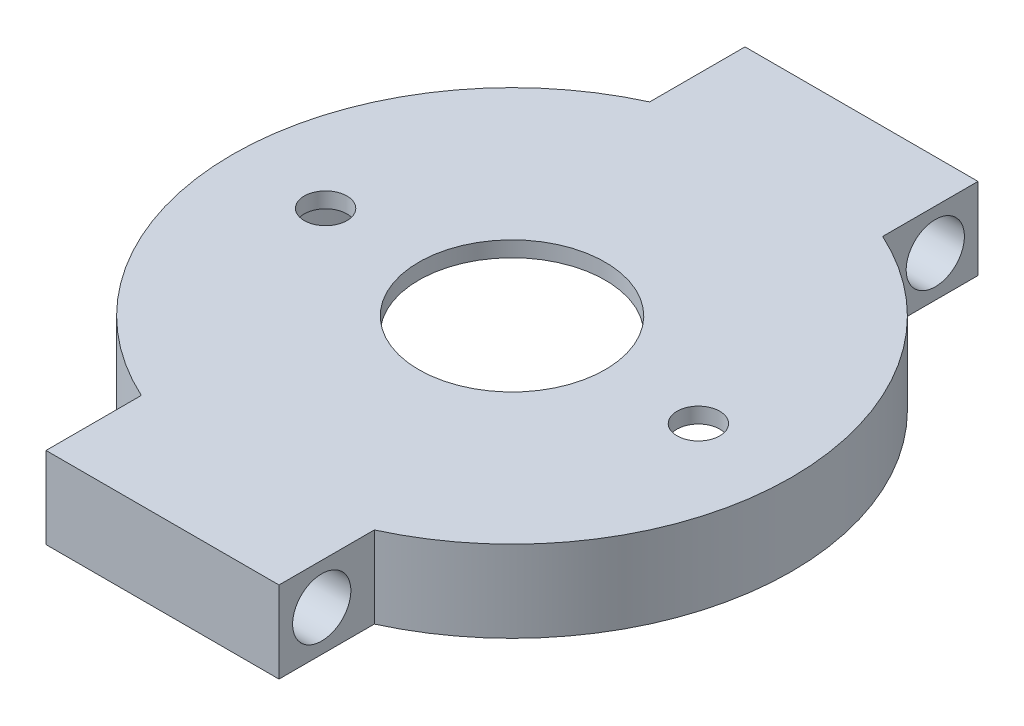
SolidWorks part; units mm, degrees
material "1345 Alloy"
ref_plane "Front Plane" through (0, 0, 0) normal (0, 0, 1) x (1, 0, 0)
ref_plane "Top Plane" through (0, 0, 0) normal (0, 1, 0) x (1, 0, 0)
ref_plane "Right Plane" through (0, 0, 0) normal (1, 0, 0) x (0, 0, -1)
sketch "Sketch1" plane through (0, 0, 0) normal (0, 1, 0) x (1, 0, 0)
  line L0 (-19.05, 57.15) -> (19.05, 57.15)
  line L1 (-19.05, -57.15) -> (19.05, -57.15)
  line L4 (-19.05, 57.15) -> (-19.05, 41.5622)
  line L6 (0, 64.6445) -> (0, -62.188) construction
  line L9 (19.05, -57.15) -> (19.05, -41.5622)
  line L10 (19.05, 57.15) -> (19.05, 41.5622)
  line L13 (-19.05, -57.15) -> (-19.05, -41.5622)
  line L17 (0, 45.72) -> (0, -45.72) construction
  circle A0 centre (0, 0) radius 39.37
  arc A1 (-19.05, 41.5622) -> (-19.05, -41.5622) centre (0, 0) ccw
  arc A3 (19.05, 41.5622) -> (19.05, -41.5622) centre (0, 0) cw
  dimension "D1" = 78.74
  dimension "D2" = 0
  dimension "D3" = 39.37
  dimension "D5" = 6.35
  dimension "D4" = 38.1
extrude "Boss-Extrude1" add sketch "Sketch1" along normal blind 13.335
sketch "Sketch2" plane through (-19.05, 0, 0) normal (-1, 0, 0) x (0, 0, 1)
  line L1 (57.15, 6.6675) -> (-57.15, 6.6675) construction
  line L3 (-57.15, 13.335) -> (-57.15, 0) construction
  line L4 (57.15, 13.335) -> (57.15, 0) construction
  circle A0 centre (50.165, 6.6675) radius 4.7625
  circle A1 centre (-50.165, 6.6675) radius 4.7625
  dimension "D1" = 9.525
  dimension "D2" = 6.985
  dimension "D3" = 6.985
extrude "Cut-Extrude1" cut sketch "Sketch2" against normal through all contours A0 L1 | L1 A0 | A1
ref_plane "Plane1" through (0, 0, 0) normal (-1, 0, 0) x (0, 0, 1)
sketch "Sketch4" plane through (0, 13.335, 0) normal (0, 1, 0) x (1, 0, 0)
  circle A0 centre (0, 0) radius 39.37
extrude "Boss-Extrude2" add sketch "Sketch4" against normal blind 2.54
sketch "Sketch5" plane through (0, 13.335, 0) normal (0, 1, 0) x (1, 0, 0)
  circle A0 centre (0, 0) radius 30.48
  circle A1 centre (30.48, 0) radius 3.4925
  circle A2 centre (-30.48, 0) radius 3.4925
  dimension "D1" = 6.985
  dimension "D2" = 60.96
extrude "Cut-Extrude2" cut sketch "Sketch5" against normal blind 2.54 contours A0 A1 | A0 A1 | A0 A2 | A0 A2
sketch "Sketch6" plane through (0, 13.335, 0) normal (0, 1, 0) x (1, 0, 0)
  circle A0 centre (0, 0) radius 15.24
  dimension "D1" = 30.48
extrude "Cut-Extrude3" cut sketch "Sketch6" against normal blind 2.54
